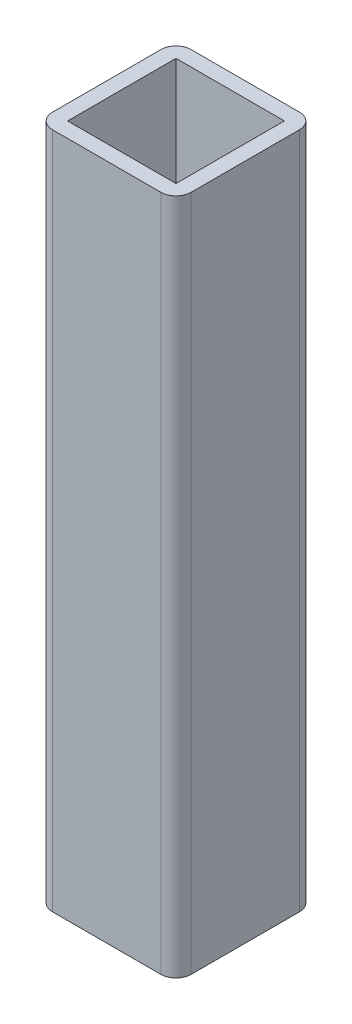
SolidWorks part; units mm, degrees
material "Gray Cast Iron"
ref_plane "Front Plane" through (0, 0, 0) normal (0, 0, 1) x (1, 0, 0)
ref_plane "Top Plane" through (0, 0, 0) normal (0, 1, 0) x (1, 0, 0)
ref_plane "Right Plane" through (0, 0, 0) normal (1, 0, 0) x (0, 0, -1)
sketch "Sketch1" plane through (0, 0, 0) normal (0, 1, 0) x (1, 0, 0)
  line L1 (2.8, 0) -> (22.8, 0)
  line L2 (0, -2.8) -> (0, -22.8)
  line L3 (2.8, -25.6) -> (22.8, -25.6)
  line L4 (25.6, -2.8) -> (25.6, -22.8)
  arc A0 (22.8, 0) -> (25.6, -2.8) centre (22.8, -2.8) cw
  arc A1 (22.8, -25.6) -> (25.6, -22.8) centre (22.8, -22.8) ccw
  arc A2 (0, -22.8) -> (2.8, -25.6) centre (2.8, -22.8) ccw
  arc A3 (2.8, 0) -> (0, -2.8) centre (2.8, -2.8) ccw
  point P7 (25.6, 0)
  point P10 (25.6, -25.6)
  point P15 (0, 0)
  dimension "D2" = 2.8
  dimension "D1" = 25.6
extrude "Boss-Extrude1" add sketch "Sketch1" along normal blind 65 and the other way blind 60
sketch "Sketch3" plane through (0, -60, 0) normal (0, -1, 0) x (-1, 0, 0)
  line L4 (-2.8, -2.8) -> (-22.8, -2.8)
  line L5 (-2.8, -2.8) -> (-2.8, -22.8)
  line L6 (-2.8, -22.8) -> (-22.8, -22.8)
  line L7 (-22.8, -2.8) -> (-22.8, -22.8)
  line L8 (-2.8, -2.8) -> (-22.8, -22.8) construction
  line L9 (-2.8, -22.8) -> (-22.8, -2.8) construction
  point P6 (-12.8, -12.8)
extrude "Cut-Extrude1" cut sketch "Sketch3" against normal blind 1040.5
